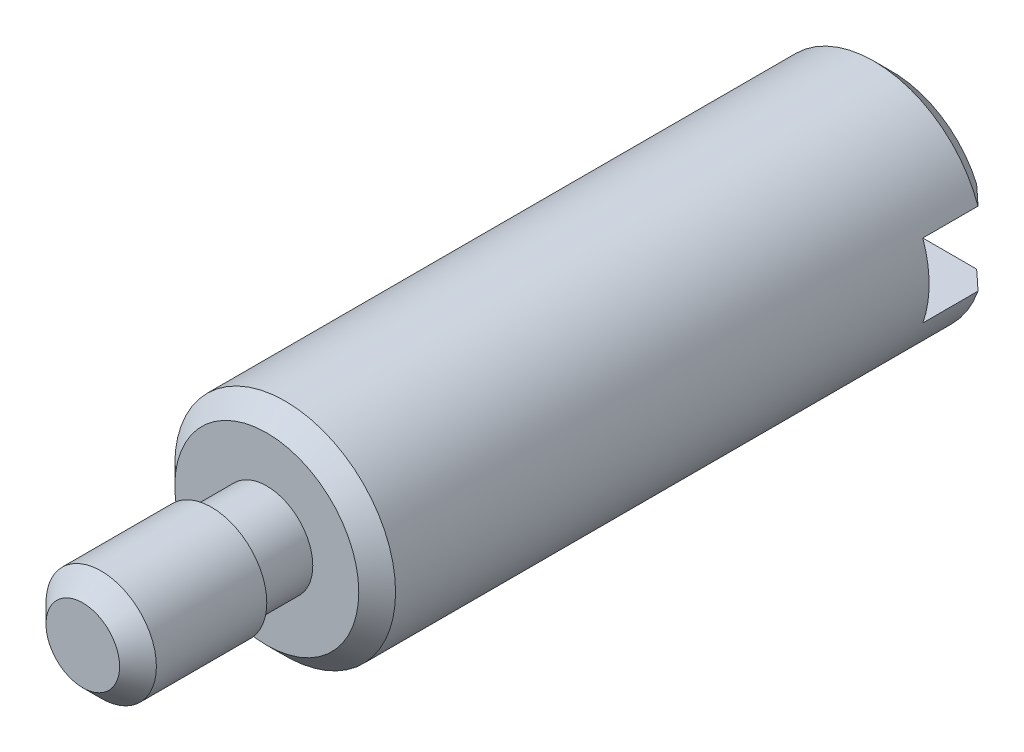
SolidWorks part; units mm, degrees
material "SUS304 (无磁性)"
ref_plane "前视基准面" through (0, 0, 0) normal (0, 0, 1) x (1, 0, 0)
ref_plane "上视基准面" through (0, 0, 0) normal (0, 1, 0) x (1, 0, 0)
ref_plane "右视基准面" through (0, 0, 0) normal (1, 0, 0) x (0, 0, -1)
sketch "草图1" plane through (0, 0, 0) normal (0, 0, 1) x (1, 0, 0)
  circle A0 centre (0, 0) radius 3
  dimension "D1" = 6
extrude "拉伸1" add sketch "草图1" along normal blind 17
sketch "草图2" plane through (0, 0, 17) normal (0, 0, 1) x (1, 0, 0)
  circle A0 centre (0, 0) radius 1.5
  dimension "D1" = 3
extrude "拉伸2" add sketch "草图2" along normal blind 5
cosmetic thread "装饰螺纹线1" parameters "D2"=2.5
chamfer "倒角1" distance 0.5 angle 45 1 edges at (1.5, 0, 22)
sketch "草图3" plane through (0, 0, 17) normal (0, 0, 1) x (1, 0, 0)
  circle A0 centre (0, 0) radius 1.25
  circle A1 centre (0, 0) radius 1.5 construction
  circle A2 centre (0, 0) radius 1.5
  dimension "D1" = 2.5
extrude "拉伸3" cut sketch "草图3" along normal blind 1.5
sketch "草图4" plane through (0, 0, 0) normal (1, 0, 0) x (0, 0, -1)
  line L0 (0, -3) -> (0, 3) construction
  line L1 (0, 1) -> (-2, 1)
  line L2 (0, 1) -> (0, -1)
  line L3 (0, -1) -> (-2, -1)
  line L4 (-2, 1) -> (-2, -1)
  line L5 (0, 0) -> (-2, 0) construction
  dimension "D1" = 2
  dimension "D2" = 2
extrude "拉伸4" cut sketch "草图4" against normal mid plane 20
chamfer "倒角2" distance 0.5 angle 45 3 edges at (3, 0, 17) (0, -3, 0) (0, 3, 0)
